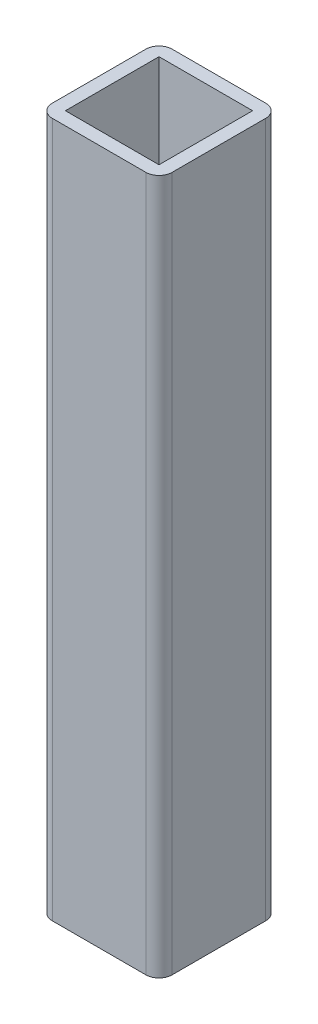
SolidWorks part; units mm, degrees
material "Plain Carbon Steel"
ref_plane "Front Plane" through (0, 0, 0) normal (0, 0, 1) x (1, 0, 0)
ref_plane "Top Plane" through (0, 0, 0) normal (0, 1, 0) x (1, 0, 0)
ref_plane "Right Plane" through (0, 0, 0) normal (1, 0, 0) x (0, 0, -1)
sketch "Sketch1" plane through (0, 0, 0) normal (0, 1, 0) x (1, 0, 0)
  line L1 (2.8, 0) -> (22.8, 0)
  line L2 (0, -2.8) -> (0, -22.8)
  line L3 (2.8, -25.6) -> (22.8, -25.6)
  line L4 (25.6, -2.8) -> (25.6, -22.8)
  arc A0 (22.8, 0) -> (25.6, -2.8) centre (22.8, -2.8) cw
  arc A1 (22.8, -25.6) -> (25.6, -22.8) centre (22.8, -22.8) ccw
  arc A2 (0, -22.8) -> (2.8, -25.6) centre (2.8, -22.8) ccw
  arc A3 (2.8, 0) -> (0, -2.8) centre (2.8, -2.8) ccw
  point P7 (25.6, 0)
  point P10 (25.6, -25.6)
  point P15 (0, 0)
  dimension "D2" = 2.8
  dimension "D1" = 25.6
extrude "Boss-Extrude1" add sketch "Sketch1" along normal blind 148.5
sketch "Sketch3" plane through (0, 0, 0) normal (0, -1, 0) x (-1, 0, 0)
  line L4 (-2.8, -2.8) -> (-22.8, -2.8)
  line L5 (-2.8, -2.8) -> (-2.8, -22.8)
  line L6 (-2.8, -22.8) -> (-22.8, -22.8)
  line L7 (-22.8, -2.8) -> (-22.8, -22.8)
  line L8 (-2.8, -2.8) -> (-22.8, -22.8) construction
  line L9 (-2.8, -22.8) -> (-22.8, -2.8) construction
  point P6 (-12.8, -12.8)
extrude "Cut-Extrude1" cut sketch "Sketch3" against normal blind 148.5
